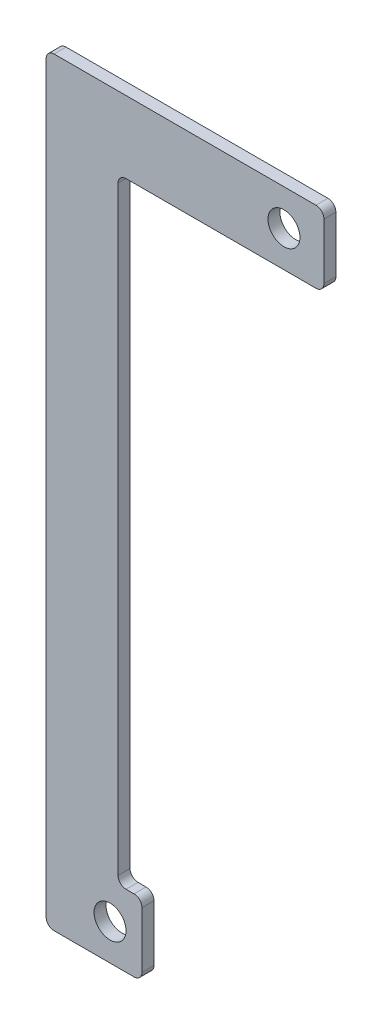
SolidWorks part; units mm, degrees
ref_plane "Front Plane" through (0, 0, 0) normal (0, 0, 1) x (1, 0, 0)
ref_plane "Top Plane" through (0, 0, 0) normal (0, 1, 0) x (1, 0, 0)
ref_plane "Right Plane" through (0, 0, 0) normal (1, 0, 0) x (0, 0, -1)
sketch "Sketch1" plane through (0, 0, 0) normal (0, 0, 1) x (1, 0, 0)
  line L0 (12, 8) -> (12, 1)
  line L1 (11, 0) -> (1, 0)
  line L2 (0, 1) -> (0, 94)
  line L3 (1, 95) -> (33.76, 95)
  line L4 (34.76, 94) -> (34.76, 87)
  line L5 (33.76, 86) -> (10, 86)
  line L6 (9, 85) -> (9, 10)
  line L7 (10, 9) -> (11, 9)
  line L8 (0.825, 0) -> (-0.825, 0) construction
  line L9 (29.76, 90.5) -> (29.76, 86) construction
  line L10 (29.76, 90.5) -> (29.76, 95) construction
  line L11 (10, 9) -> (0, 9) construction
  line L12 (8, 9) -> (8, 4.5) construction
  line L13 (8, 4.5) -> (8, 0) construction
  arc A0 (0, 94) -> (1, 95) centre (1, 94) cw
  arc A1 (12, 1) -> (11, 0) centre (11, 1) cw
  arc A2 (1, 0) -> (0, 1) centre (1, 1) cw
  arc A3 (9, 10) -> (10, 9) centre (10, 10) ccw
  arc A4 (12, 8) -> (11, 9) centre (11, 8) ccw
  arc A5 (10, 86) -> (9, 85) centre (10, 85) ccw
  arc A6 (34.76, 87) -> (33.76, 86) centre (33.76, 87) cw
  arc A7 (33.76, 95) -> (34.76, 94) centre (33.76, 94) cw
  circle A8 centre (29.76, 90.5) radius 2
  circle A9 centre (8, 4.5) radius 2
  dimension "D1" = 1
  dimension "D2" = 1
  dimension "D10" = 4
  dimension "D13" = 4
  dimension "D3" = 9
  dimension "D4" = 3
  dimension "D5" = 9
  dimension "D6" = 9
  dimension "D7" = 95
  dimension "D8" = 34.76
  dimension "D9" = 0
  dimension "D11" = 5
  dimension "D12" = 4
extrude "Boss-Extrude1" add sketch "Sketch1" along normal blind 1.5
